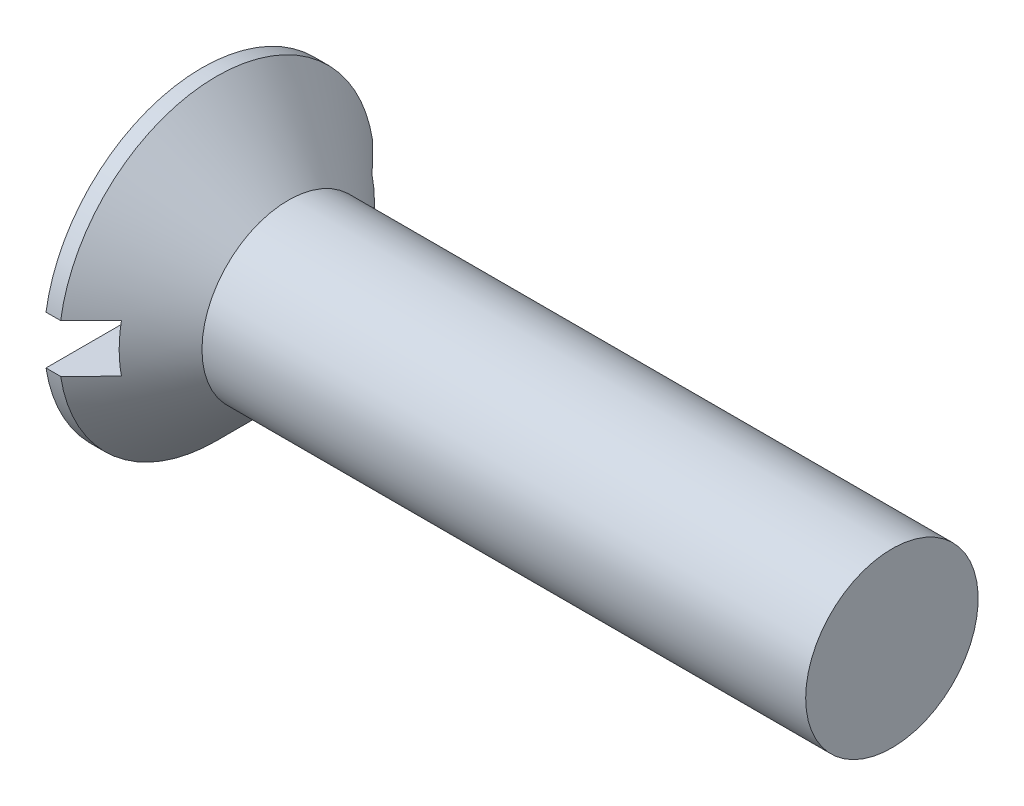
SolidWorks part; units mm, degrees
revolve "Base-Revolve" add sketch "BodySke" angle 360 about L5
sketch "BodySke" plane through (0, 0, 0) normal (0, 0, 1) x (1, 0, 0)
  line L0 (0, 0) -> (0, 9.15)
  line L1 (0, 9.15) -> (0.85, 9.15)
  line L2 (5, 5) -> (40, 5)
  line L3 (40, 5) -> (40, 0)
  line L4 (40, 0) -> (0, 0)
  line L5 (-6.35, 0) -> (82.55, 0) construction
  line L6 (5, -5) -> (40, -5) construction
  line L7 (0.85, -9.15) -> (5, -5) construction
  line L8 (0.85, 9.15) -> (5, 5)
  line L9 (0, -9.15) -> (0.85, -9.15) construction
  line L10 (6.5, 6.5875) -> (6.5, -2.9375) construction
  line L11 (5, 6.35) -> (5, -3.175) construction
  dimension "Diameter" = 10
  dimension "Length" = 40
  dimension "Head_ht" = 5
  dimension "Head_dia" = 18.3
  dimension "Head_ang" = 90
  dimension "D6" = 0.85
  dimension "Advance" = 1.5
  dimension "Thread_nom" = 35
cosmetic thread "ThreadCosmetic" parameters "Thread_length"=33.5, "Thread_minor"=8.344
extrude "Slot" cut sketch "Sketch2" against normal blind 2.6
sketch "Sketch2" plane through (0, 0, 0) normal (-1, 0, 0) x (0, 0, 1)
  line L0 (-9.15, -1.4) -> (9.15, -1.4)
  line L1 (-9.15, -1.4) -> (-9.15, 1.4)
  line L2 (9.15, 1.4) -> (-9.15, 1.4)
  line L3 (9.15, 1.4) -> (9.15, -1.4)
  dimension "Slot_width" = 2.8
  dimension "D1" = 1.4
  dimension "D2" = 18.3
  dimension "D3" = 9.15
ref_plane "Plane1" through (0, 0, 0) normal (0, 0, 1) x (1, 0, 0)
ref_plane "Plane2" through (0, 0, 0) normal (0, 1, 0) x (1, 0, 0)
ref_plane "Plane3" through (0, 0, 0) normal (1, 0, 0) x (0, 0, -1)
sketch "Sketch3" plane through (0, 0, 0) normal (-1, 0, 0) x (0, 0, 1)
  line L0 (-0.99, 4.94) -> (0.99, 4.94)
  line L1 (0.99, 4.94) -> (0.99, -4.94)
  line L2 (0.99, -4.94) -> (-0.99, -4.94)
  line L3 (-0.99, -4.94) -> (-0.99, 4.94)
  dimension "Cross_dia" = 9.88
  dimension "Cross_width" = 1.98
  dimension "D1" = 4.94
  dimension "D2" = 0.99
ref_plane "Plane4" through (5.98, 0, 0) normal (-1, 0, 0) x (0, 0, 1)
sketch "Sketch4" plane through (5.98, 0, 0) normal (-1, 0, 0) x (0, 0, 1)
  line L0 (-0.495, 0.495) -> (0.495, 0.495)
  line L3 (0.495, 0.495) -> (0.495, -0.495)
  line L4 (0.495, -0.495) -> (-0.495, -0.495)
  line L5 (-0.495, -0.495) -> (-0.495, 0.495)
  dimension "D2" = 0.99
  dimension "D1" = 0.99
  dimension "D3" = 0.495
  dimension "D4" = 0.495
loft "Cross" cut profiles "Sketch3", "Sketch4"
pattern_circular "CirPattern1" count 2 every 90 about axis through (0, 0, 0) along (1, 0, 0) of "Cross"
sketch "ThdSchSke" plane through (0, 0, 0) normal (0, 0, 1) x (1, 0, 0)
  line L0 (6.5, -4.172) -> (5.9202, -5)
  line L1 (6.5, -4.172) -> (7.0798, -5)
  line L2 (7.0798, -5) -> (7.0798, -6.25)
  line L3 (-3.175, 0) -> (5.1513, 0) construction
  line L5 (7.0798, -6.25) -> (5.9202, -6.25)
  line L6 (5.9202, -6.25) -> (5.9202, -5)
  line L7 (0, 9.15) -> (0, 1.4) construction
  dimension "Diameter" = 10
  dimension "Thread_minor" = 8.344
  dimension "Start" = 6.5
revolve "ThreadSchematic" [suppressed] cut sketch "ThdSchSke" angle 360 about L3
pattern_linear "ThdSchPat" [suppressed]
equation "\"D1@Sketch3\" = \"Cross_dia@Sketch3\" / 2"
equation "\"D2@Sketch3\" = \"Cross_width@Sketch3\" / 2"
equation "\"D1@Sketch4\" = \"Cross_width@Sketch3\" *.5"
equation "\"D2@Sketch4\" = \"D1@Sketch4\""
equation "\"D4@Sketch4\" = \"D2@Sketch4\" / 2"
equation "\"D3@Sketch4\" = \"D1@Sketch4\" / 2"
equation "\"D1@Sketch2\" = \"Slot_width@Sketch2\" / 2"
equation "\"D2@Sketch2\" = \"Head_dia@BodySke\""
equation "\"D3@Sketch2\" = \"D2@Sketch2\" / 2"
equation "\"Thread_length@ThreadCosmetic\" = ((sgn( (\"Length@BodySke\" - \"Advance@BodySke\" - \"Head_ht@BodySke\" ) - \"Thread_nom@BodySke\" )-1)*( (\"Length@BodySke\" - \"Advance@BodySke\" - \"Head_ht@BodySke\" ) - \"Thread_nom@BodySke\" ))/-2+ \"Thread_nom@BodySke\""
equation "\"Thread_minor@ThdSchSke\" = \"Thread_minor@ThreadCosmetic\""
equation "\"Diameter@ThdSchSke\" = \"Diameter@BodySke\""
equation "\"Overcut@ThdSchSke\" = \"Diameter@BodySke\" * 1.25"
equation "\"Start@ThdSchSke\" = 0.000001 + \"Length@BodySke\" - \"Thread_length@ThreadCosmetic\"  '---Countersunk---"
equation "\"Num_threads@ThdSchPat\" = int( \"Thread_length@ThreadCosmetic\" / \"Advance@BodySke\" + 0.999 )  + 1"
equation "\"Advance@ThdSchPat\" = \"Thread_length@ThreadCosmetic\" /  (\"Num_threads@ThdSchPat\" - 1) 'relax it"
